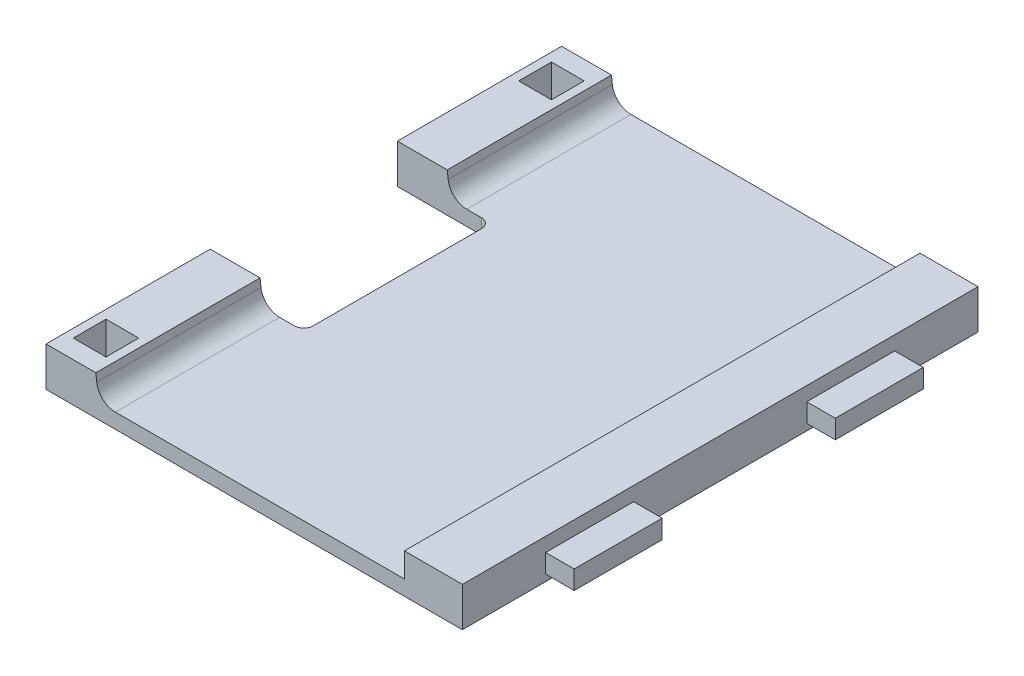
SolidWorks part; units mm, degrees
ref_plane "Plano frontal" through (0, 0, 0) normal (0, 0, 1) x (1, 0, 0)
ref_plane "Plano superior" through (0, 0, 0) normal (0, 1, 0) x (1, 0, 0)
ref_plane "Plano direito" through (0, 0, 0) normal (1, 0, 0) x (0, 0, -1)
sketch "Esboço1" plane through (0, 0, 0) normal (0, 0, 1) x (1, 0, 0)
  line L0 (0, 0) -> (40.7, 0)
  line L1 (40.7, 0) -> (40.7, 4.2)
  line L2 (40.7, 4.2) -> (34.5, 4.2)
  line L3 (34.5, 4.2) -> (34.5, 1.6)
  line L4 (34.5, 1.6) -> (3.6146, 1.6)
  line L16 (1.5316, 4.2) -> (1.6279, 3.3697)
  line L17 (34.5, 4.2) -> (-0.4869, 4.2) construction
  line L18 (1.5316, 4.2) -> (-3.796, 4.2)
  line L19 (-3.796, 4.2) -> (-3.796, 0)
  line L21 (0, 0) -> (-3.796, 0)
  arc A3 (1.6279, 3.3697) -> (3.6146, 1.6) centre (3.6146, 3.6) ccw
  point P19 (-5.436, 4.6019)
  point P22 (1.833, 1.6)
  dimension "D8" = 1.6279
  dimension "D9" = 4.6019
  dimension "D11" = 5.436
  dimension "D15" = 2
  dimension "D2" = 40.7
  dimension "D3" = 4.2
  dimension "D4" = 1.6
  dimension "D5" = 6.2
  dimension "D6" = 32.9684
  dimension "D7" = 5.3276
extrude "Ressalto-extrusão1" add sketch "Esboço1" along normal blind 55.1
sketch "Esboço5" plane through (40.7, 0, 0) normal (1, 0, 0) x (0, 0, -1)
  line L0 (-27.55, 0) -> (-27.55, 7.5229) construction
  line L1 (-18.3, 2.7) -> (-8.9, 2.7)
  line L2 (-18.3, 2.7) -> (-18.3, 0.7)
  line L3 (-18.3, 0.7) -> (-8.9, 0.7)
  line L4 (-8.9, 2.7) -> (-8.9, 0.7)
  line L5 (-55.1, 0) -> (0, 0) construction
  line L6 (0, 0) -> (0, 4.2) construction
  line L7 (-36.8, 0.7) -> (-46.2, 0.7)
  line L8 (-46.2, 2.7) -> (-46.2, 0.7)
  line L9 (-36.8, 2.7) -> (-46.2, 2.7)
  line L10 (-36.8, 2.7) -> (-36.8, 0.7)
  dimension "D1" = 2
  dimension "D2" = 9.4
  dimension "D3" = 8.9
  dimension "D4" = 0.7
extrude "Ressalto-extrusão2" add sketch "Esboço5" along normal blind 3.05
sketch "Esboço8" plane through (0, 4.2, 0) normal (0, 1, 0) x (1, 0, 0)
  line L0 (-3.796, -27.55) -> (1.5316, -27.55) construction
  line L1 (-3.796, -55.1) -> (-3.796, 0) construction
  line L2 (-2.8822, -53.1) -> (-2.8822, -49.6)
  line L3 (-2.8822, -53.1) -> (0.6178, -53.1)
  line L4 (0.6178, -53.1) -> (0.6178, -49.6)
  line L5 (0.6178, -49.6) -> (-2.8822, -49.6)
  line L6 (-2.8822, -49.6) -> (-3.796, -49.6) construction
  line L7 (0.6178, -49.6) -> (1.5316, -49.6) construction
  line L8 (1.5316, -55.1) -> (1.5316, 0) construction
  line L9 (-3.796, -55.1) -> (-3.796, 0) construction
  line L10 (-2.8822, -2) -> (0.6178, -2)
  line L11 (0.6178, -2) -> (0.6178, -5.5)
  line L12 (0.6178, -5.5) -> (-2.8822, -5.5)
  line L13 (-2.8822, -2) -> (-2.8822, -5.5)
  dimension "D1" = 2
  dimension "D2" = 3.5
  dimension "D3" = 3.5
extrude "Corte-extrusão6" cut sketch "Esboço8" against normal blind 3.5
sketch "Esboço9" plane through (0, 0, 0) normal (0, -1, 0) x (1, 0, 0)
  line L0 (-3.796, 55.1) -> (-3.796, 0) construction
  line L1 (-3.796, 37.55) -> (6.204, 37.55)
  line L2 (-3.796, 37.55) -> (-3.796, 17.55)
  line L3 (-3.796, 17.55) -> (6.204, 17.55)
  line L4 (6.204, 37.55) -> (6.204, 17.55)
  point P6 (-3.796, 27.55)
  dimension "D1" = 10
  dimension "D2" = 20
extrude "Corte-extrusão7" cut sketch "Esboço9" against normal through all
fillet "Filete1" radius 1 2 edges at (6.204, 0.8, 37.55) (6.204, 0.8, 17.55)
